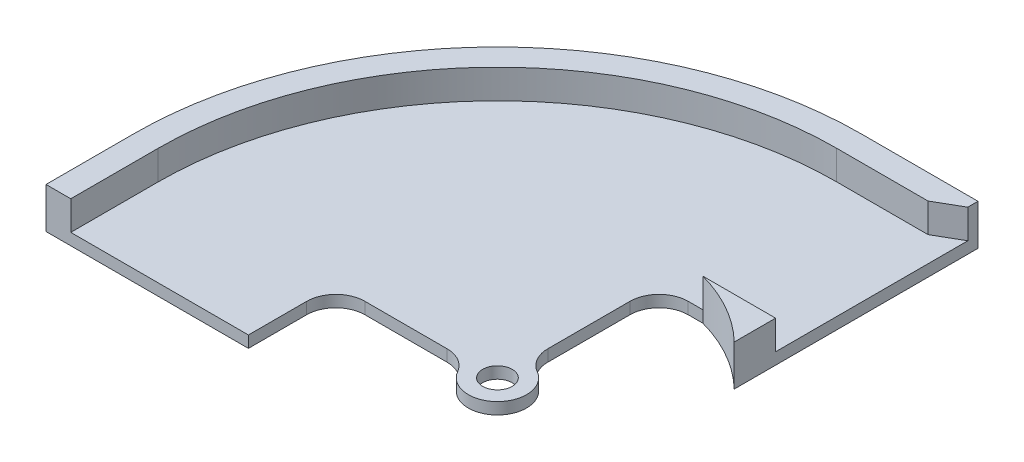
SolidWorks part; units mm, degrees
ref_plane "Front Plane" through (0, 0, 0) normal (0, 0, 1) x (1, 0, 0)
ref_plane "Top Plane" through (0, 0, 0) normal (0, 1, 0) x (1, 0, 0)
ref_plane "Right Plane" through (0, 0, 0) normal (1, 0, 0) x (0, 0, -1)
sketch "Sketch1" plane through (0, 0, 0) normal (0, 1, 0) x (1, 0, 0)
  line L1 (-62.5, 62.5) -> (62.5, 62.5)
  line L2 (-62.5, 62.5) -> (-62.5, -62.5)
  line L3 (-62.5, -62.5) -> (62.5, -62.5)
  line L4 (62.5, 62.5) -> (62.5, -62.5)
  line L5 (-62.5, 62.5) -> (62.5, -62.5) construction
  line L6 (-62.5, -62.5) -> (62.5, 62.5) construction
  circle A0 centre (62.5, -62.5) radius 55.5 construction
  point P0 (0, 0)
  dimension "D2" = 111
  dimension "D3" = 125
  dimension "D1" = 125
extrude "Boss-Extrude1" add sketch "Sketch1" along normal blind 4
sketch "Sketch7" plane through (0, 0, 0) normal (0, 1, 0) x (1, 0, 0)
  line L0 (62.5, 62.5) -> (62.5, -62.5) construction
  line L1 (62.5, -7) -> (102.5, -7)
  line L2 (62.5, -7) -> (62.5, 62.5)
  line L3 (62.5, 62.5) -> (102.5, 62.5)
  line L4 (102.5, -7) -> (102.5, 62.5)
  line L5 (-62.5, 62.5) -> (62.5, 62.5) construction
  circle A0 centre (62.5, -62.5) radius 55.5 construction
  dimension "D1" = 40
extrude "Boss-Extrude4" add sketch "Sketch7" along normal up to surface (4 mm away) up to face at (0, 4, 0)
sketch "Sketch8" plane through (0, 0, 0) normal (0, 1, 0) x (1, 0, 0)
  line L1 (-62.5, -62.5) -> (7, -62.5)
  line L2 (-62.5, -62.5) -> (-62.5, -92.5)
  line L3 (-62.5, -92.5) -> (7, -92.5)
  line L4 (7, -62.5) -> (7, -92.5)
  circle A0 centre (62.5, -62.5) radius 55.5 construction
  dimension "D1" = 30
extrude "Boss-Extrude5" add sketch "Sketch8" along normal up to surface (4 mm away) up to face at (34.1667, 4, 2.3333)
sketch "Sketch2" plane through (0, 4, 0) normal (0, 1, 0) x (1, 0, 0)
  line L0 (-62.5, -92.5) -> (-62.5, 62.5)
  line L1 (-62.5, 62.5) -> (102.5, 62.5)
  line L3 (62.5, -62.5) -> (62.5, -7) construction
  line L5 (7, -62.5) -> (62.5, -62.5) construction
  line L6 (62.5, 54) -> (102.5, 54)
  line L7 (102.5, -7) -> (102.5, 62.5) construction
  line L8 (102.5, 54) -> (102.5, 62.5)
  line L9 (-62.5, -92.5) -> (-54, -92.5)
  line L10 (-62.5, -92.5) -> (7, -92.5) construction
  line L11 (-54, -92.5) -> (-54, -62.5)
  arc A0 (-54, -62.5) -> (62.5, 54) centre (62.5, -62.5) cw
  circle A1 centre (62.5, -62.5) radius 55.5 construction
  dimension "D1" = 111
  dimension "D2" = 61
extrude "Boss-Extrude2" add sketch "Sketch2" along normal blind 10
sketch "Sketch3" plane through (0, 4, 0) normal (0, 1, 0) x (1, 0, 0)
  circle A0 centre (62.5, -62.5) radius 10
  dimension "D1" = 20
extrude "Boss-Extrude3" add sketch "Sketch3" against normal up to surface (4 mm away) up to face at (27.375, 0, 24.875)
sketch "Sketch4" plane through (0, 4, 0) normal (0, 1, 0) x (1, 0, 0)
  circle A0 centre (62.5, -62.5) radius 5.075
  dimension "D1" = 10.15
extrude "Cut-Extrude1" cut sketch "Sketch4" against normal up to surface (4 mm away) up to face at (31.5079, 0, 29.2857)
fillet "Fillet1" radius 125 1 edges at (-62.5, 7, -62.5)
chamfer "Chamfer1" distance 5 angle 60 1 edges at (102.5, 9, -54)
sketch "Sketch9" plane through (0, 0, 0) normal (0, 1, 0) x (1, 0, 0)
  line L0 (102.5, -7) -> (102.5, -21.1932)
  line L1 (102.5, -7) -> (77.5333, -7)
  line L2 (62.5, -7) -> (102.5, -7) construction
  arc A0 (77.5333, -7) -> (102.5, -21.1932) centre (62.5, -62.5) cw
  circle A1 centre (62.5, -62.5) radius 55.5 construction
  dimension "D1" = 2
extrude "Boss-Extrude6" add sketch "Sketch9" along normal up to surface (14 mm away)
fillet "Fillet2" radius 10 4 edges at (62.5, 2, 7) (62.5, 2, 52.5) (52.5, 2, 62.5) (7, 2, 62.5)
